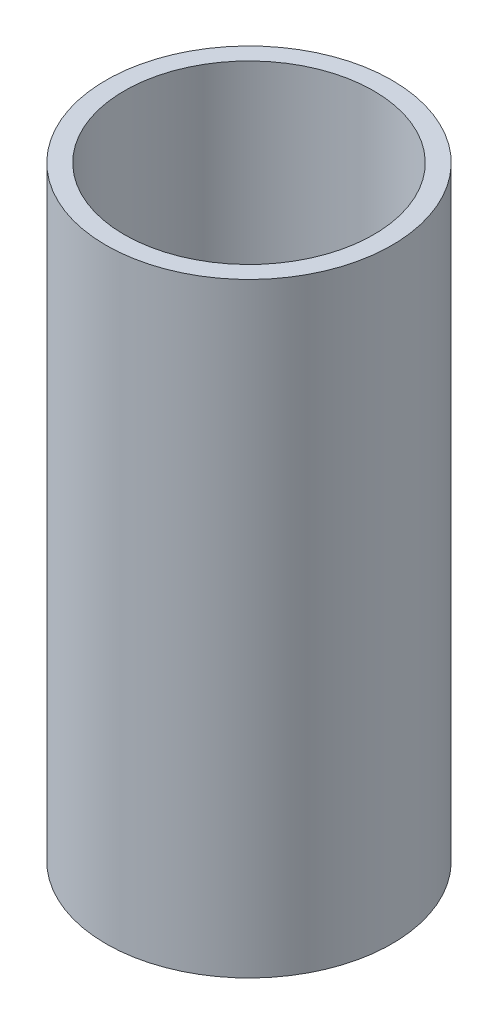
SolidWorks part; units mm, degrees
ref_plane "Front Plane" through (0, 0, 0) normal (0, 0, 1) x (1, 0, 0)
ref_plane "Top Plane" through (0, 0, 0) normal (0, 1, 0) x (1, 0, 0)
ref_plane "Right Plane" through (0, 0, 0) normal (1, 0, 0) x (0, 0, -1)
sketch "Sketch1" plane through (0, 0, 0) normal (0, 1, 0) x (1, 0, 0)
  circle A0 centre (0, 0) radius 39
  dimension "D1" = 78
extrude "Boss-Extrude1" add sketch "Sketch1" along normal blind 165
sketch "Sketch2" plane through (0, 0, 0) normal (0, -1, 0) x (1, 0, 0)
  circle A0 centre (0, 0) radius 31.5
  dimension "D1" = 63
extrude "Cut-Extrude1" cut sketch "Sketch2" against normal blind 25
sketch "Sketch3" plane through (0, 165, 0) normal (0, 1, 0) x (1, 0, 0)
  circle A0 centre (0, 0) radius 34
  circle A1 centre (0, 0) radius 39 construction
  dimension "D1" = 5
extrude "Cut-Extrude2" cut sketch "Sketch3" against normal blind 140
